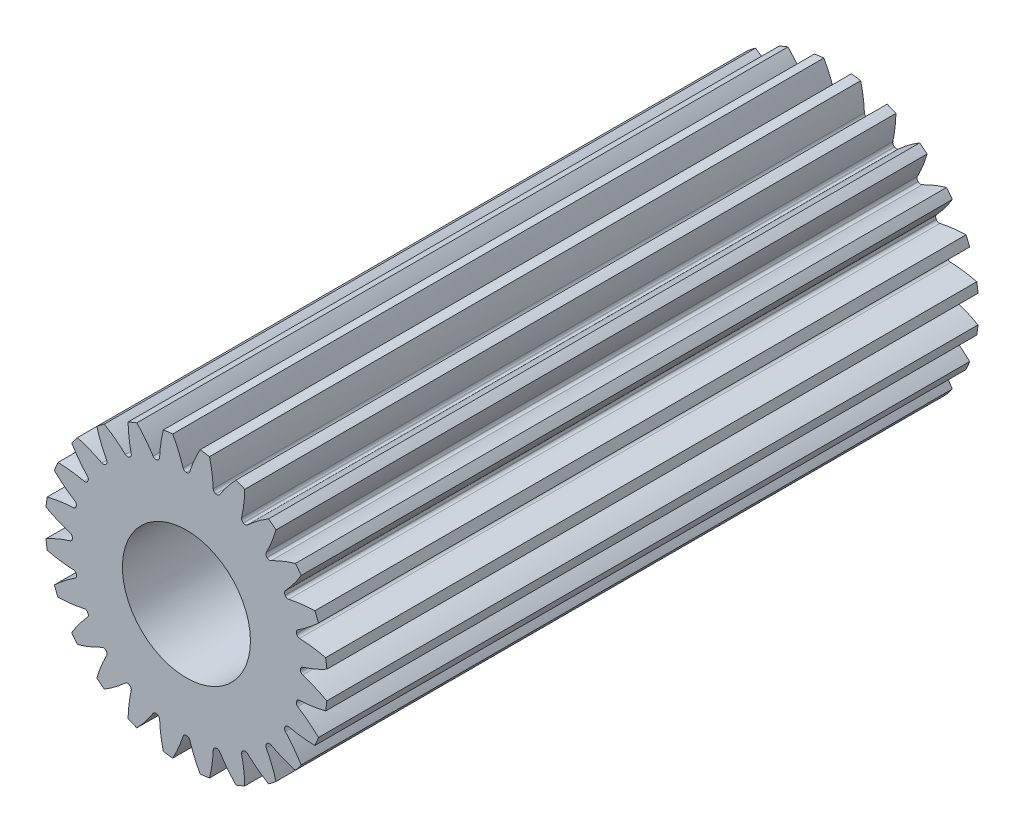
SolidWorks part; units mm, degrees
ref_plane "Front Plane" through (0, 0, 0) normal (0, 0, 1) x (1, 0, 0)
ref_plane "Top Plane" through (0, 0, 0) normal (0, 1, 0) x (1, 0, 0)
ref_plane "Right Plane" through (0, 0, 0) normal (1, 0, 0) x (0, 0, -1)
sketch "Sketch1" plane through (0, 0, 0) normal (0, 0, 1) x (1, 0, 0)
  line L0 (-304.8, 0) -> (304.8, 0) construction
  circle A0 centre (0, 0) radius 6.5 construction
  circle A1 centre (0, 0) radius 6 construction
  circle A2 centre (0, 0) radius 5.25 construction
  circle A3 centre (0, 0) radius 4 construction
  circle A4 centre (0, 0) radius 2 construction
  dimension "D2" = 0.5
  dimension "D3" = 1.25
  dimension "D1" = 1.25
sketch "Sketch2" plane through (0, 0, 0) normal (1, 0, 0) x (0, 0, -1)
  line L0 (0, 0) -> (-3, 0) construction
  line L1 (-3, 0) -> (-7, 0) construction
  dimension "Overall Width" = 7
  dimension "Face Width" = 3
sketch "Sketch4" plane through (0, 0, 0) normal (1, 0, 0) x (0, 0, -1)
  line L0 (-7, 2) -> (-7, 4) construction
  line L1 (-7, 4) -> (-3, 4) construction
  line L2 (-3, 4) -> (-3, 6.5)
  line L3 (-3, 6.5) -> (0, 6.5)
  line L4 (0, 6.5) -> (0, 2)
  line L5 (-3, 4) -> (-3, 0) construction
  line L6 (0, 6.5) -> (0, -6.5) construction
  line L7 (-3, 4) -> (0, 4) construction
  line L8 (-3, 4) -> (-3, 2)
  line L9 (-3, 2) -> (0, 2) construction
  line L10 (0, 2) -> (0, 0)
  line L11 (0, 0) -> (-3, 0)
  line L12 (-7, 2) -> (0, 2) construction
  line L13 (-3, 0) -> (-3, 2)
revolve "Revolve1" add sketch "Sketch4" angle 360 about L1
sketch "Sketch7" plane through (0, 0, 3) normal (0, 0, 1) x (1, 0, 0)
  line L0 (0, 0) -> (0, 6.5) construction
  line L1 (0.3924, 5.9872) -> (0.6056, 6.4717) construction
  line L3 (0.8484, 6.4444) -> (0.7832, 5.9487) construction
  line L4 (0.7832, 5.9487) -> (0.6853, 5.2051) construction
  line L5 (0, 0) -> (0.6853, 5.2051) construction
  line L6 (0.3924, 5.9872) -> (0, 0) construction
  line L7 (0.3924, 5.9872) -> (0.4251, 6.4861) construction
  line L8 (0.3924, 5.9872) -> (0, 0) construction
  circle A0 centre (0, 0) radius 6.5 construction
  arc A1 (-0.0123, 5.25) -> (0.0123, 5.25) centre (0, 0) cw
  circle A2 centre (0, 0) radius 5.25 construction
  arc A3 (-0.3924, 5.9872) -> (0.3924, 5.9872) centre (0, 0) cw construction
  circle A4 centre (0, 0) radius 6 construction
  arc A5 (1.065, 6.4122) -> (0.6309, 6.4693) centre (0, 0) ccw construction
  arc A6 (0.3924, 5.9872) -> (1.1705, 5.8847) centre (0, 0) cw construction
  arc A7 (-0.6309, 6.4693) -> (0.6309, 6.4693) centre (0, 0) cw
  arc A8 (0.1559, 5.3554) -> (0.6309, 6.4693) centre (5.8843, 3.5707) cw
  arc A9 (-0.1559, 5.3554) -> (-0.6309, 6.4693) centre (-5.8843, 3.5707) ccw
  arc A10 (-0.0123, 5.25) -> (-0.1559, 5.3554) centre (-0.0126, 5.4) cw
  arc A11 (0.0123, 5.25) -> (0.1559, 5.3554) centre (0.0126, 5.4) ccw
  point P26 (-0.1237, 5.2485)
  point P29 (0.1237, 5.2485)
  dimension "D4" = 0.15
  dimension "D5" = 6
  dimension "D3" = 20
  dimension "D1" = 1.5708
  dimension "D2" = 0.7854
extrude "Cut-Extrude2" cut sketch "Sketch7" against normal through all
pattern_circular "CirPattern1" count 24 over 360 about axis through (0, 0, 0) along (0, 0, 1) of "Cut-Extrude2"
sketch "Sketch8" plane through (0, 0, 3) normal (0, 0, 1) x (1, 0, 0)
  arc A144 (-1.5366, 5.1326) -> (-2.2838, 6.0856) centre (-6.6079, 1.926) ccw
  arc A145 (-2.2838, 6.0856) -> (-2.6883, 5.918) centre (0, 0) ccw
  arc A146 (-2.6883, 5.918) -> (-2.5427, 4.7158) centre (3.3106, 6.0344) ccw
  arc A147 (-2.6143, 4.5528) -> (-2.5427, 4.7158) centre (-2.689, 4.6829) ccw
  arc A148 (-2.6143, 4.5528) -> (-2.6356, 4.5405) centre (0, 0) ccw
  arc A149 (-2.8127, 4.56) -> (-2.6356, 4.5405) centre (-2.7109, 4.6702) ccw
  arc A150 (-2.8127, 4.56) -> (-3.781, 5.2871) centre (-6.8813, 0.1502) ccw
  arc A151 (-3.781, 5.2871) -> (-4.1284, 5.0206) centre (0, 0) ccw
  arc A152 (-4.1284, 5.0206) -> (-3.6766, 3.897) centre (1.636, 6.6857) ccw
  arc A153 (-3.7036, 3.721) -> (-3.6766, 3.897) centre (-3.8094, 3.8273) ccw
  arc A154 (-3.7036, 3.721) -> (-3.721, 3.7036) centre (0, 0) ccw
  arc A155 (-3.897, 3.6766) -> (-3.721, 3.7036) centre (-3.8273, 3.8094) ccw
  arc A156 (-3.897, 3.6766) -> (-5.0206, 4.1284) centre (-6.6857, -1.636) ccw
  arc A157 (-5.0206, 4.1284) -> (-5.2871, 3.781) centre (0, 0) ccw
  arc A158 (-5.2871, 3.781) -> (-4.56, 2.8127) centre (-0.1502, 6.8813) ccw
  arc A159 (-4.5405, 2.6356) -> (-4.56, 2.8127) centre (-4.6702, 2.7109) ccw
  arc A160 (-4.5405, 2.6356) -> (-4.5528, 2.6143) centre (0, 0) ccw
  arc A161 (-4.7158, 2.5427) -> (-4.5528, 2.6143) centre (-4.6829, 2.689) ccw
  arc A162 (-4.7158, 2.5427) -> (-5.918, 2.6883) centre (-6.0344, -3.3106) ccw
  arc A163 (-5.918, 2.6883) -> (-6.0856, 2.2838) centre (0, 0) ccw
  arc A164 (-6.0856, 2.2838) -> (-5.1326, 1.5366) centre (-1.926, 6.6079) ccw
  arc A165 (-5.0679, 1.3707) -> (-5.1326, 1.5366) centre (-5.2127, 1.4098) ccw
  arc A166 (-5.0679, 1.3707) -> (-5.0743, 1.3469) centre (0, 0) ccw
  arc A167 (-5.2132, 1.2355) -> (-5.0743, 1.3469) centre (-5.2193, 1.3854) ccw
  arc A168 (-5.2132, 1.2355) -> (-6.4122, 1.065) centre (-4.972, -4.7596) ccw
  arc A169 (-6.4122, 1.065) -> (-6.4693, 0.6309) centre (0, 0) ccw
  arc A170 (-6.4693, 0.6309) -> (-5.3554, 0.1559) centre (-3.5707, 5.8843) ccw
  arc A171 (-5.25, 0.0123) -> (-5.3554, 0.1559) centre (-5.4, 0.0126) ccw
  arc A172 (-5.25, 0.0123) -> (-5.25, -0.0123) centre (0, 0) ccw
  arc A173 (-5.3554, -0.1559) -> (-5.25, -0.0123) centre (-5.4, -0.0126) ccw
  arc A174 (-5.3554, -0.1559) -> (-6.4693, -0.6309) centre (-3.5707, -5.8843) ccw
  arc A175 (-6.4693, -0.6309) -> (-6.4122, -1.065) centre (0, 0) ccw
  arc A176 (-6.4122, -1.065) -> (-5.2132, -1.2355) centre (-4.972, 4.7596) ccw
  arc A177 (-5.0743, -1.3469) -> (-5.2132, -1.2355) centre (-5.2193, -1.3854) ccw
  arc A178 (-5.0743, -1.3469) -> (-5.0679, -1.3707) centre (0, 0) ccw
  arc A179 (-5.1326, -1.5366) -> (-5.0679, -1.3707) centre (-5.2127, -1.4098) ccw
  arc A180 (-5.1326, -1.5366) -> (-6.0856, -2.2838) centre (-1.926, -6.6079) ccw
  arc A181 (-6.0856, -2.2838) -> (-5.918, -2.6883) centre (0, 0) ccw
  arc A182 (-5.918, -2.6883) -> (-4.7158, -2.5427) centre (-6.0344, 3.3106) ccw
  arc A183 (-4.5528, -2.6143) -> (-4.7158, -2.5427) centre (-4.6829, -2.689) ccw
  arc A184 (-4.5528, -2.6143) -> (-4.5405, -2.6356) centre (0, 0) ccw
  arc A185 (-4.56, -2.8127) -> (-4.5405, -2.6356) centre (-4.6702, -2.7109) ccw
  arc A186 (-4.56, -2.8127) -> (-5.2871, -3.781) centre (-0.1502, -6.8813) ccw
  arc A187 (-5.2871, -3.781) -> (-5.0206, -4.1284) centre (0, 0) ccw
  arc A188 (-5.0206, -4.1284) -> (-3.897, -3.6766) centre (-6.6857, 1.636) ccw
  arc A189 (-3.721, -3.7036) -> (-3.897, -3.6766) centre (-3.8273, -3.8094) ccw
  arc A190 (-3.721, -3.7036) -> (-3.7036, -3.721) centre (0, 0) ccw
  arc A191 (-3.6766, -3.897) -> (-3.7036, -3.721) centre (-3.8094, -3.8273) ccw
  arc A192 (-3.6766, -3.897) -> (-4.1284, -5.0206) centre (1.636, -6.6857) ccw
  arc A193 (-4.1284, -5.0206) -> (-3.781, -5.2871) centre (0, 0) ccw
  arc A194 (-3.781, -5.2871) -> (-2.8127, -4.56) centre (-6.8813, -0.1502) ccw
  arc A195 (-2.6356, -4.5405) -> (-2.8127, -4.56) centre (-2.7109, -4.6702) ccw
  arc A196 (-2.6356, -4.5405) -> (-2.6143, -4.5528) centre (0, 0) ccw
  arc A197 (-2.5427, -4.7158) -> (-2.6143, -4.5528) centre (-2.689, -4.6829) ccw
  arc A198 (-2.5427, -4.7158) -> (-2.6883, -5.918) centre (3.3106, -6.0344) ccw
  arc A199 (-2.6883, -5.918) -> (-2.2838, -6.0856) centre (0, 0) ccw
  arc A200 (-2.2838, -6.0856) -> (-1.5366, -5.1326) centre (-6.6079, -1.926) ccw
  arc A201 (-1.3707, -5.0679) -> (-1.5366, -5.1326) centre (-1.4098, -5.2127) ccw
  arc A202 (-1.3707, -5.0679) -> (-1.3469, -5.0743) centre (0, 0) ccw
  arc A203 (-1.2355, -5.2132) -> (-1.3469, -5.0743) centre (-1.3854, -5.2193) ccw
  arc A204 (-1.2355, -5.2132) -> (-1.065, -6.4122) centre (4.7596, -4.972) ccw
  arc A205 (-1.065, -6.4122) -> (-0.6309, -6.4693) centre (0, 0) ccw
  arc A206 (-0.6309, -6.4693) -> (-0.1559, -5.3554) centre (-5.8843, -3.5707) ccw
  arc A207 (-0.0123, -5.25) -> (-0.1559, -5.3554) centre (-0.0126, -5.4) ccw
  arc A208 (-0.0123, -5.25) -> (0.0123, -5.25) centre (0, 0) ccw
  arc A209 (0.1559, -5.3554) -> (0.0123, -5.25) centre (0.0126, -5.4) ccw
  arc A210 (0.1559, -5.3554) -> (0.6309, -6.4693) centre (5.8843, -3.5707) ccw
  arc A211 (0.6309, -6.4693) -> (1.065, -6.4122) centre (0, 0) ccw
  arc A212 (1.065, -6.4122) -> (1.2355, -5.2132) centre (-4.7596, -4.972) ccw
  arc A213 (1.3469, -5.0743) -> (1.2355, -5.2132) centre (1.3854, -5.2193) ccw
  arc A214 (1.3469, -5.0743) -> (1.3707, -5.0679) centre (0, 0) ccw
  arc A215 (1.5366, -5.1326) -> (1.3707, -5.0679) centre (1.4098, -5.2127) ccw
  arc A216 (1.5366, -5.1326) -> (2.2838, -6.0856) centre (6.6079, -1.926) ccw
  arc A217 (2.2838, -6.0856) -> (2.6883, -5.918) centre (0, 0) ccw
  arc A218 (2.6883, -5.918) -> (2.5427, -4.7158) centre (-3.3106, -6.0344) ccw
  arc A219 (2.6143, -4.5528) -> (2.5427, -4.7158) centre (2.689, -4.6829) ccw
  arc A220 (2.6143, -4.5528) -> (2.6356, -4.5405) centre (0, 0) ccw
  arc A221 (2.8127, -4.56) -> (2.6356, -4.5405) centre (2.7109, -4.6702) ccw
  arc A222 (2.8127, -4.56) -> (3.781, -5.2871) centre (6.8813, -0.1502) ccw
  arc A223 (3.781, -5.2871) -> (4.1284, -5.0206) centre (0, 0) ccw
  arc A224 (4.1284, -5.0206) -> (3.6766, -3.897) centre (-1.636, -6.6857) ccw
  arc A225 (3.7036, -3.721) -> (3.6766, -3.897) centre (3.8094, -3.8273) ccw
  arc A226 (3.7036, -3.721) -> (3.721, -3.7036) centre (0, 0) ccw
  arc A227 (3.897, -3.6766) -> (3.721, -3.7036) centre (3.8273, -3.8094) ccw
  arc A228 (3.897, -3.6766) -> (5.0206, -4.1284) centre (6.6857, 1.636) ccw
  arc A229 (5.0206, -4.1284) -> (5.2871, -3.781) centre (0, 0) ccw
  arc A230 (5.2871, -3.781) -> (4.56, -2.8127) centre (0.1502, -6.8813) ccw
  arc A231 (4.5405, -2.6356) -> (4.56, -2.8127) centre (4.6702, -2.7109) ccw
  arc A232 (4.5405, -2.6356) -> (4.5528, -2.6143) centre (0, 0) ccw
  arc A233 (4.7158, -2.5427) -> (4.5528, -2.6143) centre (4.6829, -2.689) ccw
  arc A234 (4.7158, -2.5427) -> (5.918, -2.6883) centre (6.0344, 3.3106) ccw
  arc A235 (5.918, -2.6883) -> (6.0856, -2.2838) centre (0, 0) ccw
  arc A236 (6.0856, -2.2838) -> (5.1326, -1.5366) centre (1.926, -6.6079) ccw
  arc A237 (5.0679, -1.3707) -> (5.1326, -1.5366) centre (5.2127, -1.4098) ccw
  arc A238 (5.0679, -1.3707) -> (5.0743, -1.3469) centre (0, 0) ccw
  arc A239 (5.2132, -1.2355) -> (5.0743, -1.3469) centre (5.2193, -1.3854) ccw
  arc A240 (5.2132, -1.2355) -> (6.4122, -1.065) centre (4.972, 4.7596) ccw
  arc A241 (6.4122, -1.065) -> (6.4693, -0.6309) centre (0, 0) ccw
  arc A242 (6.4693, -0.6309) -> (5.3554, -0.1559) centre (3.5707, -5.8843) ccw
  arc A243 (5.25, -0.0123) -> (5.3554, -0.1559) centre (5.4, -0.0126) ccw
  arc A244 (5.25, -0.0123) -> (5.25, 0.0123) centre (0, 0) ccw
  arc A245 (5.3554, 0.1559) -> (5.25, 0.0123) centre (5.4, 0.0126) ccw
  arc A246 (5.3554, 0.1559) -> (6.4693, 0.6309) centre (3.5707, 5.8843) ccw
  arc A247 (6.4693, 0.6309) -> (6.4122, 1.065) centre (0, 0) ccw
  arc A248 (6.4122, 1.065) -> (5.2132, 1.2355) centre (4.972, -4.7596) ccw
  arc A249 (5.0743, 1.3469) -> (5.2132, 1.2355) centre (5.2193, 1.3854) ccw
  arc A250 (5.0743, 1.3469) -> (5.0679, 1.3707) centre (0, 0) ccw
  arc A251 (5.1326, 1.5366) -> (5.0679, 1.3707) centre (5.2127, 1.4098) ccw
  arc A252 (5.1326, 1.5366) -> (6.0856, 2.2838) centre (1.926, 6.6079) ccw
  arc A253 (6.0856, 2.2838) -> (5.918, 2.6883) centre (0, 0) ccw
  arc A254 (5.918, 2.6883) -> (4.7158, 2.5427) centre (6.0344, -3.3106) ccw
  arc A255 (4.5528, 2.6143) -> (4.7158, 2.5427) centre (4.6829, 2.689) ccw
  arc A256 (4.5528, 2.6143) -> (4.5405, 2.6356) centre (0, 0) ccw
  arc A257 (4.56, 2.8127) -> (4.5405, 2.6356) centre (4.6702, 2.7109) ccw
  arc A258 (4.56, 2.8127) -> (5.2871, 3.781) centre (0.1502, 6.8813) ccw
  arc A259 (5.2871, 3.781) -> (5.0206, 4.1284) centre (0, 0) ccw
  arc A260 (5.0206, 4.1284) -> (3.897, 3.6766) centre (6.6857, -1.636) ccw
  arc A261 (3.721, 3.7036) -> (3.897, 3.6766) centre (3.8273, 3.8094) ccw
  arc A262 (3.721, 3.7036) -> (3.7036, 3.721) centre (0, 0) ccw
  arc A263 (3.6766, 3.897) -> (3.7036, 3.721) centre (3.8094, 3.8273) ccw
  arc A264 (3.6766, 3.897) -> (4.1284, 5.0206) centre (-1.636, 6.6857) ccw
  arc A265 (4.1284, 5.0206) -> (3.781, 5.2871) centre (0, 0) ccw
  arc A266 (3.781, 5.2871) -> (2.8127, 4.56) centre (6.8813, 0.1502) ccw
  arc A267 (2.6356, 4.5405) -> (2.8127, 4.56) centre (2.7109, 4.6702) ccw
  arc A268 (2.6356, 4.5405) -> (2.6143, 4.5528) centre (0, 0) ccw
  arc A269 (2.5427, 4.7158) -> (2.6143, 4.5528) centre (2.689, 4.6829) ccw
  arc A270 (2.5427, 4.7158) -> (2.6883, 5.918) centre (-3.3106, 6.0344) ccw
  arc A271 (2.6883, 5.918) -> (2.2838, 6.0856) centre (0, 0) ccw
  arc A272 (2.2838, 6.0856) -> (1.5366, 5.1326) centre (6.6079, 1.926) ccw
  arc A273 (1.3707, 5.0679) -> (1.5366, 5.1326) centre (1.4098, 5.2127) ccw
  arc A274 (1.3707, 5.0679) -> (1.3469, 5.0743) centre (0, 0) ccw
  arc A275 (1.2355, 5.2132) -> (1.3469, 5.0743) centre (1.3854, 5.2193) ccw
  arc A276 (1.2355, 5.2132) -> (1.065, 6.4122) centre (-4.7596, 4.972) ccw
  arc A277 (1.065, 6.4122) -> (0.6309, 6.4693) centre (0, 0) ccw
  arc A278 (0.6309, 6.4693) -> (0.1559, 5.3554) centre (5.8843, 3.5707) ccw
  arc A279 (0.0123, 5.25) -> (0.1559, 5.3554) centre (0.0126, 5.4) ccw
  arc A280 (0.0123, 5.25) -> (-0.0123, 5.25) centre (0, 0) ccw
  arc A281 (-0.1559, 5.3554) -> (-0.0123, 5.25) centre (-0.0126, 5.4) ccw
  arc A282 (-0.1559, 5.3554) -> (-0.6309, 6.4693) centre (-5.8843, 3.5707) ccw
  arc A283 (-0.6309, 6.4693) -> (-1.065, 6.4122) centre (0, 0) ccw
  arc A284 (-1.065, 6.4122) -> (-1.2355, 5.2132) centre (4.7596, 4.972) ccw
  arc A285 (-1.3469, 5.0743) -> (-1.2355, 5.2132) centre (-1.3854, 5.2193) ccw
  arc A286 (-1.3469, 5.0743) -> (-1.3707, 5.0679) centre (0, 0) ccw
  arc A287 (-1.5366, 5.1326) -> (-1.3707, 5.0679) centre (-1.4098, 5.2127) ccw
  arc A288 (-1.5366, 5.1326) -> (-2.2838, 6.0856) centre (-6.6079, 1.926) ccw
  arc A289 (-2.2838, 6.0856) -> (-2.6883, 5.918) centre (0, 0) ccw
  arc A290 (-2.6883, 5.918) -> (-2.5427, 4.7158) centre (3.3106, 6.0344) ccw
  arc A291 (-2.6143, 4.5528) -> (-2.5427, 4.7158) centre (-2.689, 4.6829) ccw
  arc A292 (-2.6143, 4.5528) -> (-2.6356, 4.5405) centre (0, 0) ccw
  arc A293 (-2.8127, 4.56) -> (-2.6356, 4.5405) centre (-2.7109, 4.6702) ccw
  arc A294 (-2.8127, 4.56) -> (-3.781, 5.2871) centre (-6.8813, 0.1502) ccw
  arc A295 (-3.781, 5.2871) -> (-4.1284, 5.0206) centre (0, 0) ccw
  arc A296 (-4.1284, 5.0206) -> (-3.6766, 3.897) centre (1.636, 6.6857) ccw
  arc A297 (-3.7036, 3.721) -> (-3.6766, 3.897) centre (-3.8094, 3.8273) ccw
  arc A298 (-3.7036, 3.721) -> (-3.721, 3.7036) centre (0, 0) ccw
  arc A299 (-3.897, 3.6766) -> (-3.721, 3.7036) centre (-3.8273, 3.8094) ccw
  arc A300 (-3.897, 3.6766) -> (-5.0206, 4.1284) centre (-6.6857, -1.636) ccw
  arc A301 (-5.0206, 4.1284) -> (-5.2871, 3.781) centre (0, 0) ccw
  arc A302 (-5.2871, 3.781) -> (-4.56, 2.8127) centre (-0.1502, 6.8813) ccw
  arc A303 (-4.5405, 2.6356) -> (-4.56, 2.8127) centre (-4.6702, 2.7109) ccw
  arc A304 (-4.5405, 2.6356) -> (-4.5528, 2.6143) centre (0, 0) ccw
  arc A305 (-4.7158, 2.5427) -> (-4.5528, 2.6143) centre (-4.6829, 2.689) ccw
  arc A306 (-4.7158, 2.5427) -> (-5.918, 2.6883) centre (-6.0344, -3.3106) ccw
  arc A307 (-5.918, 2.6883) -> (-6.0856, 2.2838) centre (0, 0) ccw
  arc A308 (-6.0856, 2.2838) -> (-5.1326, 1.5366) centre (-1.926, 6.6079) ccw
  arc A309 (-5.0679, 1.3707) -> (-5.1326, 1.5366) centre (-5.2127, 1.4098) ccw
  arc A310 (-5.0679, 1.3707) -> (-5.0743, 1.3469) centre (0, 0) ccw
  arc A311 (-5.2132, 1.2355) -> (-5.0743, 1.3469) centre (-5.2193, 1.3854) ccw
  arc A312 (-5.2132, 1.2355) -> (-6.4122, 1.065) centre (-4.972, -4.7596) ccw
  arc A313 (-6.4122, 1.065) -> (-6.4693, 0.6309) centre (0, 0) ccw
  arc A314 (-6.4693, 0.6309) -> (-5.3554, 0.1559) centre (-3.5707, 5.8843) ccw
  arc A315 (-5.25, 0.0123) -> (-5.3554, 0.1559) centre (-5.4, 0.0126) ccw
  arc A316 (-5.25, 0.0123) -> (-5.25, -0.0123) centre (0, 0) ccw
  arc A317 (-5.3554, -0.1559) -> (-5.25, -0.0123) centre (-5.4, -0.0126) ccw
  arc A318 (-5.3554, -0.1559) -> (-6.4693, -0.6309) centre (-3.5707, -5.8843) ccw
  arc A319 (-6.4693, -0.6309) -> (-6.4122, -1.065) centre (0, 0) ccw
  arc A320 (-6.4122, -1.065) -> (-5.2132, -1.2355) centre (-4.972, 4.7596) ccw
  arc A321 (-5.0743, -1.3469) -> (-5.2132, -1.2355) centre (-5.2193, -1.3854) ccw
  arc A322 (-5.0743, -1.3469) -> (-5.0679, -1.3707) centre (0, 0) ccw
  arc A323 (-5.1326, -1.5366) -> (-5.0679, -1.3707) centre (-5.2127, -1.4098) ccw
  arc A324 (-5.1326, -1.5366) -> (-6.0856, -2.2838) centre (-1.926, -6.6079) ccw
  arc A325 (-6.0856, -2.2838) -> (-5.918, -2.6883) centre (0, 0) ccw
  arc A326 (-5.918, -2.6883) -> (-4.7158, -2.5427) centre (-6.0344, 3.3106) ccw
  arc A327 (-4.5528, -2.6143) -> (-4.7158, -2.5427) centre (-4.6829, -2.689) ccw
  arc A328 (-4.5528, -2.6143) -> (-4.5405, -2.6356) centre (0, 0) ccw
  arc A329 (-4.56, -2.8127) -> (-4.5405, -2.6356) centre (-4.6702, -2.7109) ccw
  arc A330 (-4.56, -2.8127) -> (-5.2871, -3.781) centre (-0.1502, -6.8813) ccw
  arc A331 (-5.2871, -3.781) -> (-5.0206, -4.1284) centre (0, 0) ccw
  arc A332 (-5.0206, -4.1284) -> (-3.897, -3.6766) centre (-6.6857, 1.636) ccw
  arc A333 (-3.721, -3.7036) -> (-3.897, -3.6766) centre (-3.8273, -3.8094) ccw
  arc A334 (-3.721, -3.7036) -> (-3.7036, -3.721) centre (0, 0) ccw
  arc A335 (-3.6766, -3.897) -> (-3.7036, -3.721) centre (-3.8094, -3.8273) ccw
  arc A336 (-3.6766, -3.897) -> (-4.1284, -5.0206) centre (1.636, -6.6857) ccw
  arc A337 (-4.1284, -5.0206) -> (-3.781, -5.2871) centre (0, 0) ccw
  arc A338 (-3.781, -5.2871) -> (-2.8127, -4.56) centre (-6.8813, -0.1502) ccw
  arc A339 (-2.6356, -4.5405) -> (-2.8127, -4.56) centre (-2.7109, -4.6702) ccw
  arc A340 (-2.6356, -4.5405) -> (-2.6143, -4.5528) centre (0, 0) ccw
  arc A341 (-2.5427, -4.7158) -> (-2.6143, -4.5528) centre (-2.689, -4.6829) ccw
  arc A342 (-2.5427, -4.7158) -> (-2.6883, -5.918) centre (3.3106, -6.0344) ccw
  arc A343 (-2.6883, -5.918) -> (-2.2838, -6.0856) centre (0, 0) ccw
  arc A344 (-2.2838, -6.0856) -> (-1.5366, -5.1326) centre (-6.6079, -1.926) ccw
  arc A345 (-1.3707, -5.0679) -> (-1.5366, -5.1326) centre (-1.4098, -5.2127) ccw
  arc A346 (-1.3707, -5.0679) -> (-1.3469, -5.0743) centre (0, 0) ccw
  arc A347 (-1.2355, -5.2132) -> (-1.3469, -5.0743) centre (-1.3854, -5.2193) ccw
  arc A348 (-1.2355, -5.2132) -> (-1.065, -6.4122) centre (4.7596, -4.972) ccw
  arc A349 (-1.065, -6.4122) -> (-0.6309, -6.4693) centre (0, 0) ccw
  arc A350 (-0.6309, -6.4693) -> (-0.1559, -5.3554) centre (-5.8843, -3.5707) ccw
  arc A351 (-0.0123, -5.25) -> (-0.1559, -5.3554) centre (-0.0126, -5.4) ccw
  arc A352 (-0.0123, -5.25) -> (0.0123, -5.25) centre (0, 0) ccw
  arc A353 (0.1559, -5.3554) -> (0.0123, -5.25) centre (0.0126, -5.4) ccw
  arc A354 (0.1559, -5.3554) -> (0.6309, -6.4693) centre (5.8843, -3.5707) ccw
  arc A355 (0.6309, -6.4693) -> (1.065, -6.4122) centre (0, 0) ccw
  arc A356 (1.065, -6.4122) -> (1.2355, -5.2132) centre (-4.7596, -4.972) ccw
  arc A357 (1.3469, -5.0743) -> (1.2355, -5.2132) centre (1.3854, -5.2193) ccw
  arc A358 (1.3469, -5.0743) -> (1.3707, -5.0679) centre (0, 0) ccw
  arc A359 (1.5366, -5.1326) -> (1.3707, -5.0679) centre (1.4098, -5.2127) ccw
  arc A360 (1.5366, -5.1326) -> (2.2838, -6.0856) centre (6.6079, -1.926) ccw
  arc A361 (2.2838, -6.0856) -> (2.6883, -5.918) centre (0, 0) ccw
  arc A362 (2.6883, -5.918) -> (2.5427, -4.7158) centre (-3.3106, -6.0344) ccw
  arc A363 (2.6143, -4.5528) -> (2.5427, -4.7158) centre (2.689, -4.6829) ccw
  arc A364 (2.6143, -4.5528) -> (2.6356, -4.5405) centre (0, 0) ccw
  arc A365 (2.8127, -4.56) -> (2.6356, -4.5405) centre (2.7109, -4.6702) ccw
  arc A366 (2.8127, -4.56) -> (3.781, -5.2871) centre (6.8813, -0.1502) ccw
  arc A367 (3.781, -5.2871) -> (4.1284, -5.0206) centre (0, 0) ccw
  arc A368 (4.1284, -5.0206) -> (3.6766, -3.897) centre (-1.636, -6.6857) ccw
  arc A369 (3.7036, -3.721) -> (3.6766, -3.897) centre (3.8094, -3.8273) ccw
  arc A370 (3.7036, -3.721) -> (3.721, -3.7036) centre (0, 0) ccw
  arc A371 (3.897, -3.6766) -> (3.721, -3.7036) centre (3.8273, -3.8094) ccw
  arc A372 (3.897, -3.6766) -> (5.0206, -4.1284) centre (6.6857, 1.636) ccw
  arc A373 (5.0206, -4.1284) -> (5.2871, -3.781) centre (0, 0) ccw
  arc A374 (5.2871, -3.781) -> (4.56, -2.8127) centre (0.1502, -6.8813) ccw
  arc A375 (4.5405, -2.6356) -> (4.56, -2.8127) centre (4.6702, -2.7109) ccw
  arc A376 (4.5405, -2.6356) -> (4.5528, -2.6143) centre (0, 0) ccw
  arc A377 (4.7158, -2.5427) -> (4.5528, -2.6143) centre (4.6829, -2.689) ccw
  arc A378 (4.7158, -2.5427) -> (5.918, -2.6883) centre (6.0344, 3.3106) ccw
  arc A379 (5.918, -2.6883) -> (6.0856, -2.2838) centre (0, 0) ccw
  arc A380 (6.0856, -2.2838) -> (5.1326, -1.5366) centre (1.926, -6.6079) ccw
  arc A381 (5.0679, -1.3707) -> (5.1326, -1.5366) centre (5.2127, -1.4098) ccw
  arc A382 (5.0679, -1.3707) -> (5.0743, -1.3469) centre (0, 0) ccw
  arc A383 (5.2132, -1.2355) -> (5.0743, -1.3469) centre (5.2193, -1.3854) ccw
  arc A384 (5.2132, -1.2355) -> (6.4122, -1.065) centre (4.972, 4.7596) ccw
  arc A385 (6.4122, -1.065) -> (6.4693, -0.6309) centre (0, 0) ccw
  arc A386 (6.4693, -0.6309) -> (5.3554, -0.1559) centre (3.5707, -5.8843) ccw
  arc A387 (5.25, -0.0123) -> (5.3554, -0.1559) centre (5.4, -0.0126) ccw
  arc A388 (5.25, -0.0123) -> (5.25, 0.0123) centre (0, 0) ccw
  arc A389 (5.3554, 0.1559) -> (5.25, 0.0123) centre (5.4, 0.0126) ccw
  arc A390 (5.3554, 0.1559) -> (6.4693, 0.6309) centre (3.5707, 5.8843) ccw
  arc A391 (6.4693, 0.6309) -> (6.4122, 1.065) centre (0, 0) ccw
  arc A392 (6.4122, 1.065) -> (5.2132, 1.2355) centre (4.972, -4.7596) ccw
  arc A393 (5.0743, 1.3469) -> (5.2132, 1.2355) centre (5.2193, 1.3854) ccw
  arc A394 (5.0743, 1.3469) -> (5.0679, 1.3707) centre (0, 0) ccw
  arc A395 (5.1326, 1.5366) -> (5.0679, 1.3707) centre (5.2127, 1.4098) ccw
  arc A396 (5.1326, 1.5366) -> (6.0856, 2.2838) centre (1.926, 6.6079) ccw
  arc A397 (6.0856, 2.2838) -> (5.918, 2.6883) centre (0, 0) ccw
  arc A398 (5.918, 2.6883) -> (4.7158, 2.5427) centre (6.0344, -3.3106) ccw
  arc A399 (4.5528, 2.6143) -> (4.7158, 2.5427) centre (4.6829, 2.689) ccw
  arc A400 (4.5528, 2.6143) -> (4.5405, 2.6356) centre (0, 0) ccw
  arc A401 (4.56, 2.8127) -> (4.5405, 2.6356) centre (4.6702, 2.7109) ccw
  arc A402 (4.56, 2.8127) -> (5.2871, 3.781) centre (0.1502, 6.8813) ccw
  arc A403 (5.2871, 3.781) -> (5.0206, 4.1284) centre (0, 0) ccw
  arc A404 (5.0206, 4.1284) -> (3.897, 3.6766) centre (6.6857, -1.636) ccw
  arc A405 (3.721, 3.7036) -> (3.897, 3.6766) centre (3.8273, 3.8094) ccw
  arc A406 (3.721, 3.7036) -> (3.7036, 3.721) centre (0, 0) ccw
  arc A407 (3.6766, 3.897) -> (3.7036, 3.721) centre (3.8094, 3.8273) ccw
  arc A408 (3.6766, 3.897) -> (4.1284, 5.0206) centre (-1.636, 6.6857) ccw
  arc A409 (4.1284, 5.0206) -> (3.781, 5.2871) centre (0, 0) ccw
  arc A410 (3.781, 5.2871) -> (2.8127, 4.56) centre (6.8813, 0.1502) ccw
  arc A411 (2.6356, 4.5405) -> (2.8127, 4.56) centre (2.7109, 4.6702) ccw
  arc A412 (2.6356, 4.5405) -> (2.6143, 4.5528) centre (0, 0) ccw
  arc A413 (2.5427, 4.7158) -> (2.6143, 4.5528) centre (2.689, 4.6829) ccw
  arc A414 (2.5427, 4.7158) -> (2.6883, 5.918) centre (-3.3106, 6.0344) ccw
  arc A415 (2.6883, 5.918) -> (2.2838, 6.0856) centre (0, 0) ccw
  arc A416 (2.2838, 6.0856) -> (1.5366, 5.1326) centre (6.6079, 1.926) ccw
  arc A417 (1.3707, 5.0679) -> (1.5366, 5.1326) centre (1.4098, 5.2127) ccw
  arc A418 (1.3707, 5.0679) -> (1.3469, 5.0743) centre (0, 0) ccw
  arc A419 (1.2355, 5.2132) -> (1.3469, 5.0743) centre (1.3854, 5.2193) ccw
  arc A420 (1.2355, 5.2132) -> (1.065, 6.4122) centre (-4.7596, 4.972) ccw
  arc A421 (1.065, 6.4122) -> (0.6309, 6.4693) centre (0, 0) ccw
  arc A422 (0.6309, 6.4693) -> (0.1559, 5.3554) centre (5.8843, 3.5707) ccw
  arc A423 (0.0123, 5.25) -> (0.1559, 5.3554) centre (0.0126, 5.4) ccw
  arc A424 (0.0123, 5.25) -> (-0.0123, 5.25) centre (0, 0) ccw
  arc A425 (-0.1559, 5.3554) -> (-0.0123, 5.25) centre (-0.0126, 5.4) ccw
  arc A426 (-0.1559, 5.3554) -> (-0.6309, 6.4693) centre (-5.8843, 3.5707) ccw
  arc A427 (-0.6309, 6.4693) -> (-1.065, 6.4122) centre (0, 0) ccw
  arc A428 (-1.065, 6.4122) -> (-1.2355, 5.2132) centre (4.7596, 4.972) ccw
  arc A429 (-1.3469, 5.0743) -> (-1.2355, 5.2132) centre (-1.3854, 5.2193) ccw
  arc A430 (-1.3469, 5.0743) -> (-1.3707, 5.0679) centre (0, 0) ccw
  arc A431 (-1.5366, 5.1326) -> (-1.3707, 5.0679) centre (-1.4098, 5.2127) ccw
  dimension "D1" = 0
extrude "Boss-Extrude1" add sketch "Sketch8" along normal blind 27
sketch "Sketch9" plane through (0, 0, 0) normal (0, 0, -1) x (-1, 0, 0)
  line L0 (-1.49, 1.55) -> (1.49, 1.55)
  circle A0 centre (0, 0) radius 2.15 construction
  arc A1 (-1.49, 1.55) -> (1.49, 1.55) centre (0, 0) ccw
  dimension "D1" = 3.7
  dimension "D2" = 4.3
extrude "Cut-Extrude3" cut sketch "Sketch9" against normal blind 10
sketch "Sketch10" plane through (0, 0, 30) normal (0, 0, 1) x (1, 0, 0)
  circle A0 centre (0, 0) radius 2.95
  dimension "D1" = 5.9
extrude "Cut-Extrude4" cut sketch "Sketch10" against normal blind 10
fillet "Fillet1" radius 0.25 3 edges at (0, -2.15, 10) (2.95, 0, 20) (0, 1.55, 10)
equation "\"D1@Sketch1\"=2.5*(\"Pitch Dia.@Sketch1\"/\"Number of Teeth@Sketch1\")"
equation "\"D1@CirPattern1\"=\"Number of Teeth@Sketch1\""
equation "\"D1@Sketch7\"=3.14159*(\"Pitch Dia.@Sketch1\"/\"Number of Teeth@Sketch1\")"
equation "\"D2@Sketch7\"=\"D1@Sketch7\"/2"
equation "\"D4@Sketch7\"=\"D1@Sketch7\"*.0955"
equation "\"D5@Sketch7\"=\"Pitch Dia.@Sketch1\"/2"
